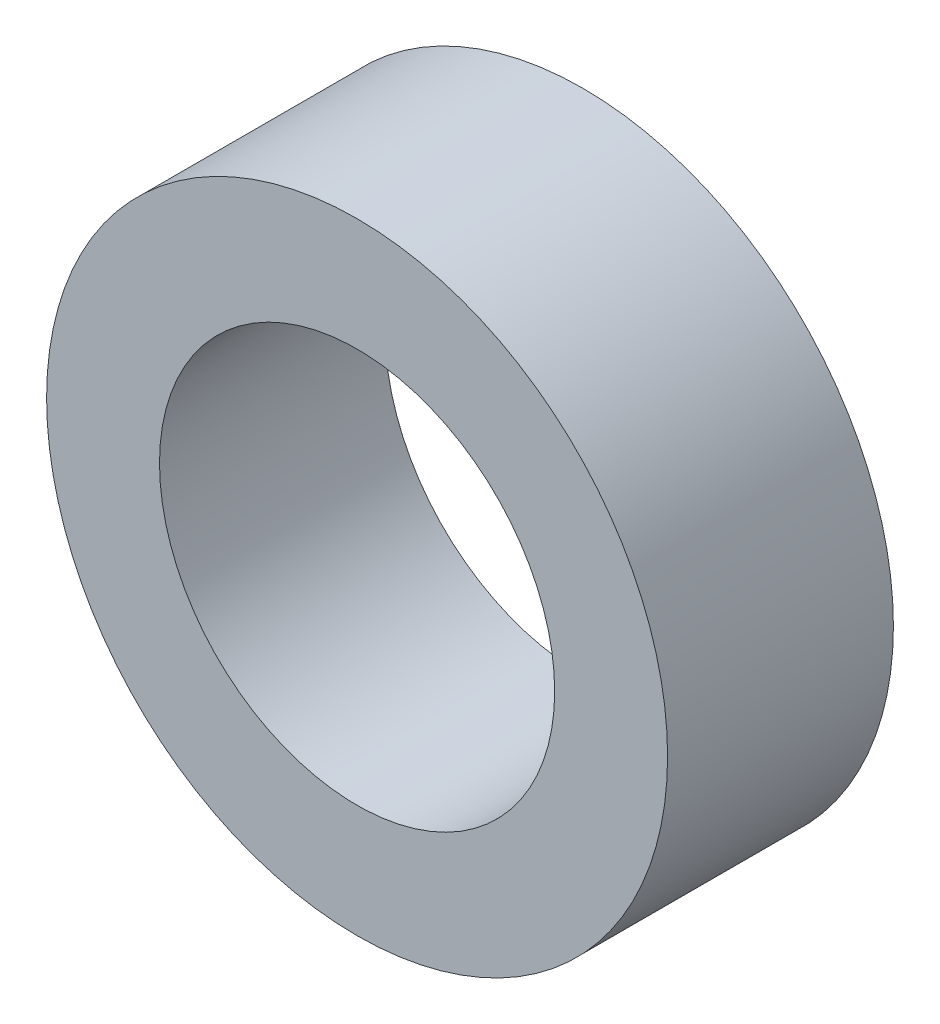
SolidWorks part; units mm, degrees
material "ABS"
ref_plane "前视基准面" through (0, 0, 0) normal (0, 0, 1) x (1, 0, 0)
ref_plane "上视基准面" through (0, 0, 0) normal (0, 1, 0) x (1, 0, 0)
ref_plane "右视基准面" through (0, 0, 0) normal (1, 0, 0) x (0, 0, -1)
sketch "草图1" plane through (0, 0, 0) normal (0, 0, 1) x (1, 0, 0)
  circle A0 centre (0, 0) radius 1.75
  circle A1 centre (0, 0) radius 2.75
  dimension "D1" = 3.5
  dimension "D2" = 5.5
extrude "凸台-拉伸1" add sketch "草图1" along normal blind 2
